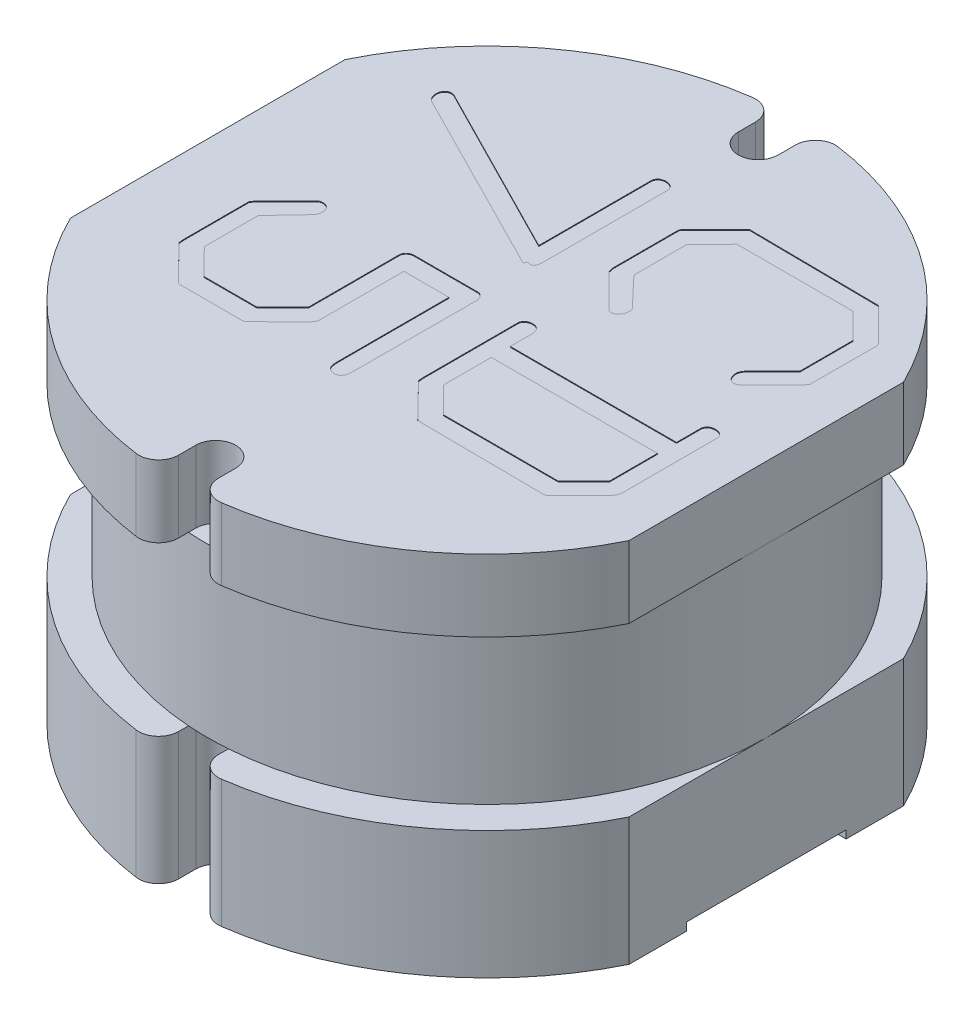
SolidWorks part; units mm, degrees
ref_plane "Front Plane" through (0, 0, 0) normal (0, 0, 1) x (1, 0, 0)
ref_plane "Top Plane" through (0, 0, 0) normal (0, 1, 0) x (1, 0, 0)
ref_plane "Right Plane" through (0, 0, 0) normal (1, 0, 0) x (0, 0, -1)
sketch "Sketch1" plane through (0, 0, 0) normal (0, 1, 0) x (1, 0, 0)
  line L0 (0, 10.5332) -> (0, 3.9) construction
  line L1 (-11.6124, 0) -> (-3.9, 0) construction
  line L2 (-3.5, 1.7205) -> (-3.5, -1.7205)
  line L3 (3.5, 1.7205) -> (3.5, -1.7205)
  line L4 (-3.9, 0) -> (-3.5, 0) construction
  line L5 (-3.5, 0) -> (3.5, 0) construction
  line L6 (3.5, 0) -> (3.9, 0) construction
  line L7 (3.9, 0) -> (12.0455, 0) construction
  line L8 (-0.25, 3.4) -> (-0.25, 3.6156)
  line L9 (0.25, 3.4) -> (0.25, 3.6156)
  line L10 (0, 3.9) -> (0, 3.15) construction
  line L11 (0, 3.15) -> (0, -3.15) construction
  line L12 (-0.25, -3.4) -> (-0.25, -3.6156)
  line L13 (0.25, -3.4) -> (0.25, -3.6156)
  line L14 (0, -3.15) -> (0, -3.9) construction
  line L15 (0, -3.9) -> (0, -14.4615) construction
  arc A0 (-3.5, -1.7205) -> (-0.5342, -3.8632) centre (0, 0) ccw
  arc A1 (-3.5, 1.7205) -> (-3.9, 0) centre (0, 0) ccw construction
  arc A2 (-3.9, 0) -> (-3.5, -1.7205) centre (0, 0) ccw construction
  arc A3 (3.9, 0) -> (3.5, 1.7205) centre (0, 0) ccw construction
  arc A4 (3.5, 1.7205) -> (0.5342, 3.8632) centre (0, 0) ccw
  arc A5 (3.5, -1.7205) -> (3.9, 0) centre (0, 0) ccw construction
  arc A6 (-0.25, 3.4) -> (0.25, 3.4) centre (0, 3.4) ccw
  arc A7 (-0.25, 3.6156) -> (-0.5342, 3.8632) centre (-0.5, 3.6156) ccw
  arc A8 (0.25, 3.6156) -> (0.5342, 3.8632) centre (0.5, 3.6156) cw
  arc A9 (0.5342, 3.8632) -> (0, 3.9) centre (0, 0) ccw construction
  arc A10 (-0.5342, 3.8632) -> (-3.5, 1.7205) centre (0, 0) ccw
  arc A11 (0, 3.9) -> (-0.5342, 3.8632) centre (0, 0) ccw construction
  arc A12 (-0.25, -3.6156) -> (-0.5342, -3.8632) centre (-0.5, -3.6156) cw
  arc A13 (-0.25, -3.4) -> (0.25, -3.4) centre (0, -3.4) cw
  arc A14 (0.25, -3.6156) -> (0.5342, -3.8632) centre (0.5, -3.6156) ccw
  arc A15 (-0.5342, -3.8632) -> (0, -3.9) centre (0, 0) ccw construction
  arc A16 (0.5342, -3.8632) -> (3.5, -1.7205) centre (0, 0) ccw
  arc A17 (0, -3.9) -> (0.5342, -3.8632) centre (0, 0) ccw construction
  point P24 (-0.25, 2.7617)
  dimension "D2" = 7.8
  dimension "D5" = 0.25
  dimension "D1" = 7
  dimension "D3" = 0.5
  dimension "D4" = 0.5
extrude "Boss-Extrude1" add sketch "Sketch1" along normal blind 1.5
sketch "Sketch2" plane through (0, 1.5, 0) normal (0, 1, 0) x (1, 0, 0)
  circle A0 centre (0, 0) radius 3.5
  dimension "D1" = 7
extrude "Boss-Extrude2" add sketch "Sketch2" along normal blind 2.1
sketch "Sketch3" plane through (0, 3.6, 0) normal (0, 1, 0) x (1, 0, 0)
  line L0 (-3.5, 1.7205) -> (-3.5, -1.7205) construction
  line L1 (-0.25, 3.4) -> (-0.25, 3.6156) construction
  line L2 (0.25, 3.4) -> (0.25, 3.6156) construction
  line L3 (3.5, 1.7205) -> (3.5, -1.7205) construction
  line L4 (0.25, -3.4) -> (0.25, -3.6156) construction
  line L5 (-0.25, -3.4) -> (-0.25, -3.6156) construction
  line L6 (-3.5, 1.7205) -> (-3.5, -1.7205)
  line L7 (-0.25, 3.4) -> (-0.25, 3.6156)
  line L8 (0.25, 3.4) -> (0.25, 3.6156)
  line L9 (3.5, 1.7205) -> (3.5, -1.7205)
  line L10 (0.25, -3.4) -> (0.25, -3.6156)
  line L11 (-0.25, -3.4) -> (-0.25, -3.6156)
  arc A0 (-0.5342, 3.8632) -> (-3.5, 1.7205) centre (0, 0) ccw construction
  arc A1 (-0.25, 3.6156) -> (-0.5342, 3.8632) centre (-0.5, 3.6156) ccw construction
  arc A2 (-0.25, 3.4) -> (0.25, 3.4) centre (0, 3.4) ccw construction
  arc A3 (0.5342, 3.8632) -> (0.25, 3.6156) centre (0.5, 3.6156) ccw construction
  arc A4 (3.5, 1.7205) -> (0.5342, 3.8632) centre (0, 0) ccw construction
  arc A5 (0.5342, -3.8632) -> (3.5, -1.7205) centre (0, 0) ccw construction
  arc A6 (0.25, -3.6156) -> (0.5342, -3.8632) centre (0.5, -3.6156) ccw construction
  arc A7 (0.25, -3.4) -> (-0.25, -3.4) centre (0, -3.4) ccw construction
  arc A8 (-0.5342, -3.8632) -> (-0.25, -3.6156) centre (-0.5, -3.6156) ccw construction
  arc A9 (-3.5, -1.7205) -> (-0.5342, -3.8632) centre (0, 0) ccw construction
  arc A10 (-0.5342, 3.8632) -> (-3.5, 1.7205) centre (0, 0) ccw
  arc A11 (-0.25, 3.6156) -> (-0.5342, 3.8632) centre (-0.5, 3.6156) ccw
  arc A12 (-0.25, 3.4) -> (0.25, 3.4) centre (0, 3.4) ccw
  arc A13 (0.5342, 3.8632) -> (0.25, 3.6156) centre (0.5, 3.6156) ccw
  arc A14 (3.5, 1.7205) -> (0.5342, 3.8632) centre (0, 0) ccw
  arc A15 (0.5342, -3.8632) -> (3.5, -1.7205) centre (0, 0) ccw
  arc A16 (0.25, -3.6156) -> (0.5342, -3.8632) centre (0.5, -3.6156) ccw
  arc A17 (0.25, -3.4) -> (-0.25, -3.4) centre (0, -3.4) ccw
  arc A18 (-0.5342, -3.8632) -> (-0.25, -3.6156) centre (-0.5, -3.6156) ccw
  arc A19 (-3.5, -1.7205) -> (-0.5342, -3.8632) centre (0, 0) ccw
extrude "Boss-Extrude3" add sketch "Sketch3" along normal blind 0.9
sketch "Sketch4" plane through (0, 0, 0) normal (0, -1, 0) x (1, 0, 0)
  line L0 (-3.5, 1) -> (3.5, 1)
  line L1 (-3.5, -1.7205) -> (-3.5, 1.7205) construction
  line L2 (3.5, -1.7205) -> (3.5, 1.7205) construction
  line L3 (3.5, 1) -> (3.5, 1.7205)
  line L4 (0.25, 3.4) -> (0.25, 3.6156) construction
  line L5 (0.25, 3.4) -> (0.25, 3.6156)
  line L6 (-3.5, 1.7205) -> (-3.5, 1)
  line L7 (-3.5, 0) -> (3.5, 0) construction
  line L8 (0, 0) -> (-3.9, 0) construction
  line L9 (0.25, -3.4) -> (0.25, -3.6156)
  line L10 (3.5, -1) -> (3.5, -1.7205)
  line L11 (-3.5, -1) -> (3.5, -1)
  line L12 (-3.5, -1.7205) -> (-3.5, -1)
  arc A0 (-0.5342, 3.8632) -> (-3.5, 1.7205) centre (0, 0) ccw construction
  arc A1 (-0.25, 3.6156) -> (-0.5342, 3.8632) centre (-0.5, 3.6156) ccw construction
  arc A2 (-0.25, 3.4) -> (0.25, 3.4) centre (0, 3.4) ccw construction
  arc A3 (0.5342, 3.8632) -> (0.25, 3.6156) centre (0.5, 3.6156) ccw construction
  arc A4 (3.5, 1.7205) -> (0.5342, 3.8632) centre (0, 0) ccw construction
  arc A5 (-0.5342, 3.8632) -> (-3.5, 1.7205) centre (0, 0) ccw
  arc A6 (-0.25, 3.6156) -> (-0.5342, 3.8632) centre (-0.5, 3.6156) ccw
  arc A7 (-0.25, 3.4) -> (0.25, 3.4) centre (0, 3.4) ccw
  arc A8 (0.5342, 3.8632) -> (0.25, 3.6156) centre (0.5, 3.6156) ccw
  arc A9 (3.5, 1.7205) -> (0.5342, 3.8632) centre (0, 0) ccw
  arc A10 (-0.25, -3.4) -> (0.25, -3.4) centre (0, -3.4) cw
  arc A11 (0.5342, -3.8632) -> (0.25, -3.6156) centre (0.5, -3.6156) cw
  arc A12 (3.5, -1.7205) -> (0.5342, -3.8632) centre (0, 0) cw
  arc A13 (-0.5342, -3.8632) -> (-3.5, -1.7205) centre (0, 0) cw
  arc A14 (-0.25, -3.6156) -> (-0.5342, -3.8632) centre (-0.5, -3.6156) cw
  arc M3 (-3.5, -1.7205) -> (-0.5342, -3.8632) centre (0, 0) ccw
  arc M4 (-0.5342, -3.8632) -> (-0.25, -3.6156) centre (-0.5, -3.6156) ccw
  line M5 (-0.25, -3.6156) -> (-0.25, -3.4)
  arc M6 (-0.25, -3.4) -> (0.25, -3.4) centre (0, -3.4) cw
  line M7 (0.25, -3.4) -> (0.25, -3.6156)
  arc M8 (0.25, -3.6156) -> (0.5342, -3.8632) centre (0.5, -3.6156) ccw
  arc M9 (0.5342, -3.8632) -> (3.5, -1.7205) centre (0, 0) ccw
  line M10 (3.5, -1.7205) -> (3.5, 1.7205)
  arc M11 (3.5, 1.7205) -> (0.5342, 3.8632) centre (0, 0) ccw
  arc M12 (0.5342, 3.8632) -> (0.25, 3.6156) centre (0.5, 3.6156) ccw
  line M13 (0.25, 3.6156) -> (0.25, 3.4)
  arc M14 (0.25, 3.4) -> (-0.25, 3.4) centre (0, 3.4) cw
  line M15 (-0.25, 3.4) -> (-0.25, 3.6156)
  arc M16 (-0.25, 3.6156) -> (-0.5342, 3.8632) centre (-0.5, 3.6156) ccw
  arc M17 (-0.5342, 3.8632) -> (-3.5, 1.7205) centre (0, 0) ccw
  line M18 (-3.5, 1.7205) -> (-3.5, -1.7205)
  dimension "D1" = 1
extrude "Boss-Extrude4" add sketch "Sketch4" along normal blind 0.1 contours L0 M18 M10 M11 M12 M13 M14 M15 M16 M17 | L11 M18 M3 M4 M5 M6 M7 M8 M9 M10
sketch "Sketch6" plane through (0, 4.5, 0) normal (0, 1, 0) x (1, 0, 0)
  line L0 (0.5, 3.8656) -> (0.5, -3.8656) construction
  line L1 (-2.5, 3.8656) -> (-2.5, -3.8656) construction
  line L2 (3.5, -1.7205) -> (3.5, 1.7205) construction
  line L3 (-3.5, 0) -> (3.5, 0) construction
  line L4 (-3.5, 1.7205) -> (-3.5, -1.7205) construction
  arc A0 (0.5342, 3.8632) -> (0.25, 3.6156) centre (0.5, 3.6156) ccw construction
  text T0 "CD" font "SWTxt" height 2.5
  text T1 "75\r\n" font "SWTxt" height 2.5
  point P10 (0, 0)
  point P11 (0, 0)
  point P12 (0, 0)
  point P15 (0.5, 3.8656)
  dimension "D1" = 3
  dimension "D2" = 3
extrude "Cut-Extrude1" cut sketch "Sketch6" against normal blind 0.01
